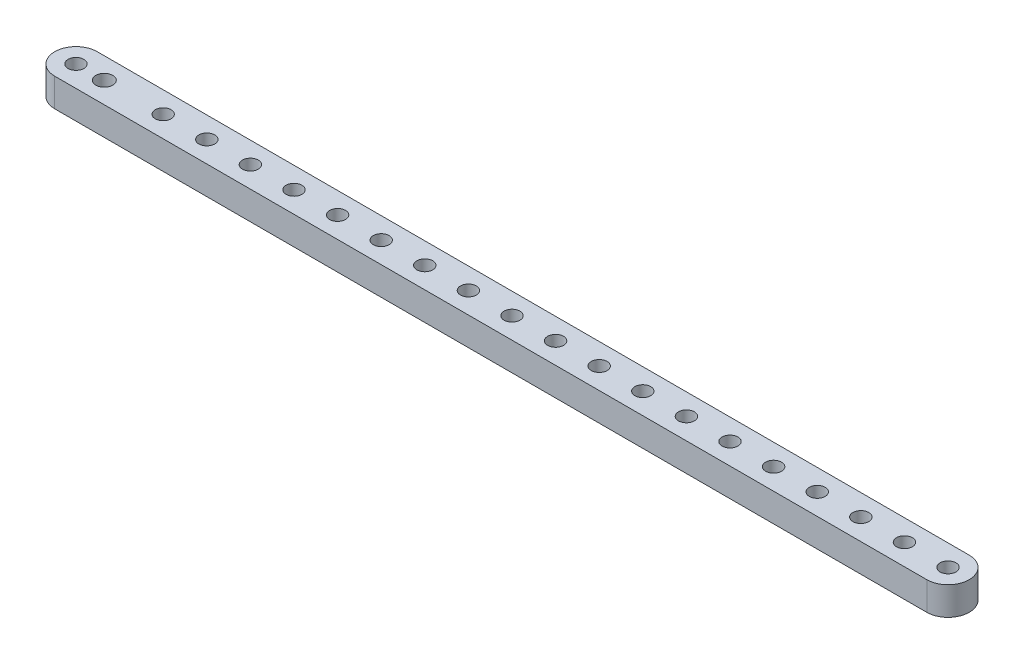
SolidWorks part; units mm, degrees
ref_plane "Front Plane" through (0, 0, 0) normal (0, 0, 1) x (1, 0, 0)
ref_plane "Top Plane" through (0, 0, 0) normal (0, 1, 0) x (1, 0, 0)
ref_plane "Right Plane" through (0, 0, 0) normal (1, 0, 0) x (0, 0, -1)
ref_plane "Plane1" through (0, 6.35, 0) normal (0, 1, 0) x (1, 0, 0)
sketch "Sketch1" plane through (0, 6.35, 0) normal (0, 1, 0) x (1, 0, 0)
  line L0 (97.79, 4.7625) -> (-97.79, 4.7625)
  line L1 (-97.79, -4.7625) -> (97.79, -4.7625)
  arc A0 (97.79, -4.7625) -> (97.79, 4.7625) centre (97.79, 0) ccw
  arc A1 (-97.79, 4.7625) -> (-97.79, -4.7625) centre (-97.79, 0) ccw
  circle A2 centre (97.79, 0) radius 1.778
  circle A3 centre (88.011, 0) radius 1.778
  circle A4 centre (78.232, 0) radius 1.778
  circle A5 centre (68.453, 0) radius 1.778
  circle A6 centre (58.674, 0) radius 1.778
  circle A7 centre (48.895, 0) radius 1.778
  circle A8 centre (39.116, 0) radius 1.778
  circle A9 centre (29.337, 0) radius 1.778
  circle A10 centre (19.558, 0) radius 1.778
  circle A11 centre (9.779, 0) radius 1.778
  circle A12 centre (0, 0) radius 1.778
  circle A13 centre (-9.779, 0) radius 1.778
  circle A14 centre (-19.558, 0) radius 1.778
  circle A15 centre (-29.337, 0) radius 1.778
  circle A16 centre (-39.116, 0) radius 1.778
  circle A17 centre (-48.895, 0) radius 1.778
  circle A18 centre (-58.674, 0) radius 1.778
  circle A19 centre (-68.453, 0) radius 1.778
  circle A20 centre (-78.232, 0) radius 1.778
  circle A21 centre (-88.011, 0) radius 1.778
  circle A22 centre (-97.79, 0) radius 1.778
extrude "Boss-Extrude1" add sketch "Sketch1" against normal blind 6.35
sketch "Sketch2" plane through (0, 6.35, 0) normal (0, 1, 0) x (1, 0, 0)
  circle A0 centre (-88.011, 0) radius 1.778
extrude "Boss-Extrude2" add sketch "Sketch2" against normal up to surface (6.35 mm away) up to face at (-97.79, 0, -1.778)
sketch "Sketch3" plane through (0, 6.35, 0) normal (0, 1, 0) x (1, 0, 0)
  line L0 (97.79, 4.7625) -> (-97.79, 4.7625) construction
  circle A0 centre (-91.44, 0) radius 1.905
  circle A1 centre (-97.79, 0) radius 1.778 construction
  dimension "D1" = 3.81
  dimension "D2" = 4.7625
  dimension "D3" = 6.35
extrude "Cut-Extrude1" cut sketch "Sketch3" against normal through all
